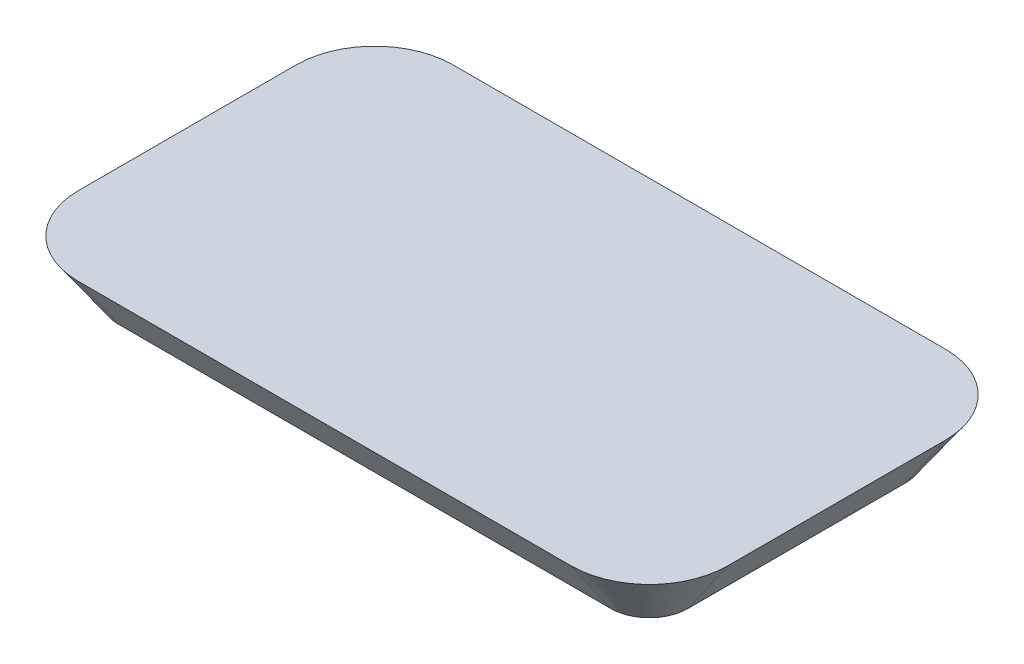
SolidWorks part; units mm, degrees
material "K1045"
ref_plane "Front Plane" through (0, 0, 0) normal (0, 0, 1) x (1, 0, 0)
ref_plane "Top Plane" through (0, 0, 0) normal (0, 1, 0) x (1, 0, 0)
ref_plane "Right Plane" through (0, 0, 0) normal (1, 0, 0) x (0, 0, -1)
sketch "Sketch1" plane through (0, 0, 0) normal (0, 1, 0) x (1, 0, 0)
  line L0 (0, 0) -> (0, 79.4322) construction
  line L1 (0, 0) -> (117.9915, 0) construction
  line L3 (-34.5, 26.25) -> (34.5, 26.25)
  line L4 (-45.5, 15.25) -> (-45.5, -15.25)
  line L5 (-34.5, -26.25) -> (34.5, -26.25)
  line L6 (45.5, 15.25) -> (45.5, -15.25)
  arc A0 (34.5, 26.25) -> (45.5, 15.25) centre (34.5, 15.25) cw
  arc A1 (34.5, -26.25) -> (45.5, -15.25) centre (34.5, -15.25) ccw
  arc A2 (-45.5, -15.25) -> (-34.5, -26.25) centre (-34.5, -15.25) ccw
  arc A3 (-34.5, 26.25) -> (-45.5, 15.25) centre (-34.5, 15.25) ccw
  point P10 (45.5, 26.25)
  point P17 (-45.5, 26.25)
  dimension "D3" = 11
  dimension "D1" = 91
  dimension "D2" = 52.5
extrude "Boss-Extrude1" add sketch "Sketch1" against normal blind 8 draft 35
